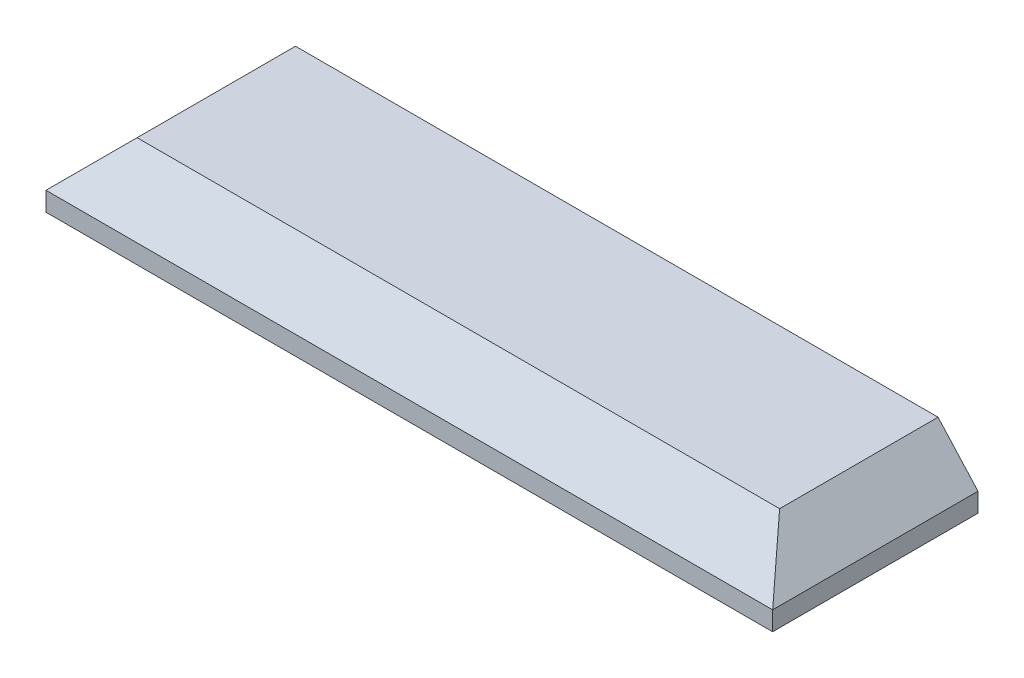
SolidWorks part; units mm, degrees
ref_plane "Front Plane" through (0, 0, 0) normal (0, 0, 1) x (1, 0, 0)
ref_plane "Top Plane" through (0, 0, 0) normal (0, 1, 0) x (1, 0, 0)
ref_plane "Right Plane" through (0, 0, 0) normal (1, 0, 0) x (0, 0, -1)
sketch "Sketch1" plane through (0, 0, 0) normal (0, 0, 1) x (1, 0, 0)
  line L1 (0, 0) -> (46, 0)
  line L2 (0, 0) -> (0, 4)
  line L3 (0, 4) -> (46, 4)
  line L4 (46, 0) -> (46, 4)
  dimension "D1" = 46
  dimension "D2" = 4
extrude "Boss-Extrude1" add sketch "Sketch1" along normal blind 13
sketch "Sketch2" plane through (46, 0, 0) normal (1, 0, 0) x (0, 0, -1)
  line L0 (-10.0297, 4) -> (-13, 1.2045)
  line L1 (-13, 4) -> (0, 4) construction
  line L2 (-13, 0) -> (-13, 4) construction
  line L3 (-13, 1.2045) -> (-13, 4)
  line L4 (-13, 4) -> (-10.0297, 4)
extrude "Cut-Extrude1" cut sketch "Sketch2" against normal blind 46
sketch "Sketch3" plane through (0, 0, 13) normal (0, 0, 1) x (1, 0, 0)
  line L0 (46, 1.2045) -> (43.4716, 4)
  line L1 (0, 4) -> (46, 4) construction
  line L2 (43.4716, 4) -> (46, 4)
  line L3 (46, 4) -> (46, 1.2045)
extrude "Cut-Extrude2" cut sketch "Sketch3" against normal blind 46
sketch "Sketch4" plane through (0, 0, 13) normal (0, 0, 1) x (1, 0, 0)
  line L3 (0, 1.2045) -> (3.0683, 4.2728)
  line L4 (3.0683, 4.2728) -> (0, 4.2728)
  line L5 (0, 4.2728) -> (0, 1.2045)
extrude "Cut-Extrude3" cut sketch "Sketch4" against normal blind 46
